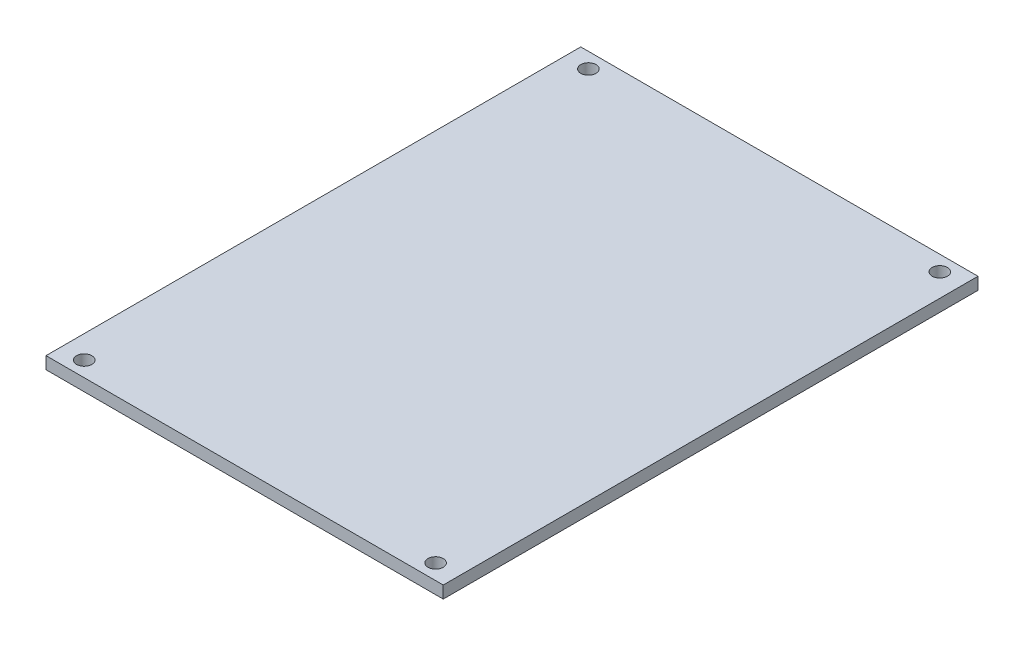
SolidWorks part; units mm, degrees
ref_plane "前视基准面" through (0, 0, 0) normal (0, 0, 1) x (1, 0, 0)
ref_plane "上视基准面" through (0, 0, 0) normal (0, 1, 0) x (1, 0, 0)
ref_plane "右视基准面" through (0, 0, 0) normal (1, 0, 0) x (0, 0, -1)
sketch "草图1" plane through (0, 0, 0) normal (0, 1, 0) x (1, 0, 0)
  line L1 (0, 70) -> (52, 70)
  line L2 (0, 70) -> (0, 0)
  line L3 (0, 0) -> (52, 0)
  line L4 (52, 70) -> (52, 0)
  line L5 (3, 2) -> (49, 2) construction
  line L6 (3, 2) -> (3, 68) construction
  line L7 (3, 68) -> (49, 68) construction
  line L8 (49, 2) -> (49, 68) construction
  circle A0 centre (3, 2) radius 1
  circle A1 centre (49, 2) radius 1
  circle A2 centre (49, 68) radius 1
  circle A3 centre (3, 68) radius 1
  dimension "D5" = 2
  dimension "D1" = 70
  dimension "D2" = 52
  dimension "D3" = 66
  dimension "D4" = 46
  dimension "D6" = 2
  dimension "D7" = 3
extrude "凸台-拉伸1" add sketch "草图1" along normal blind 1.6
